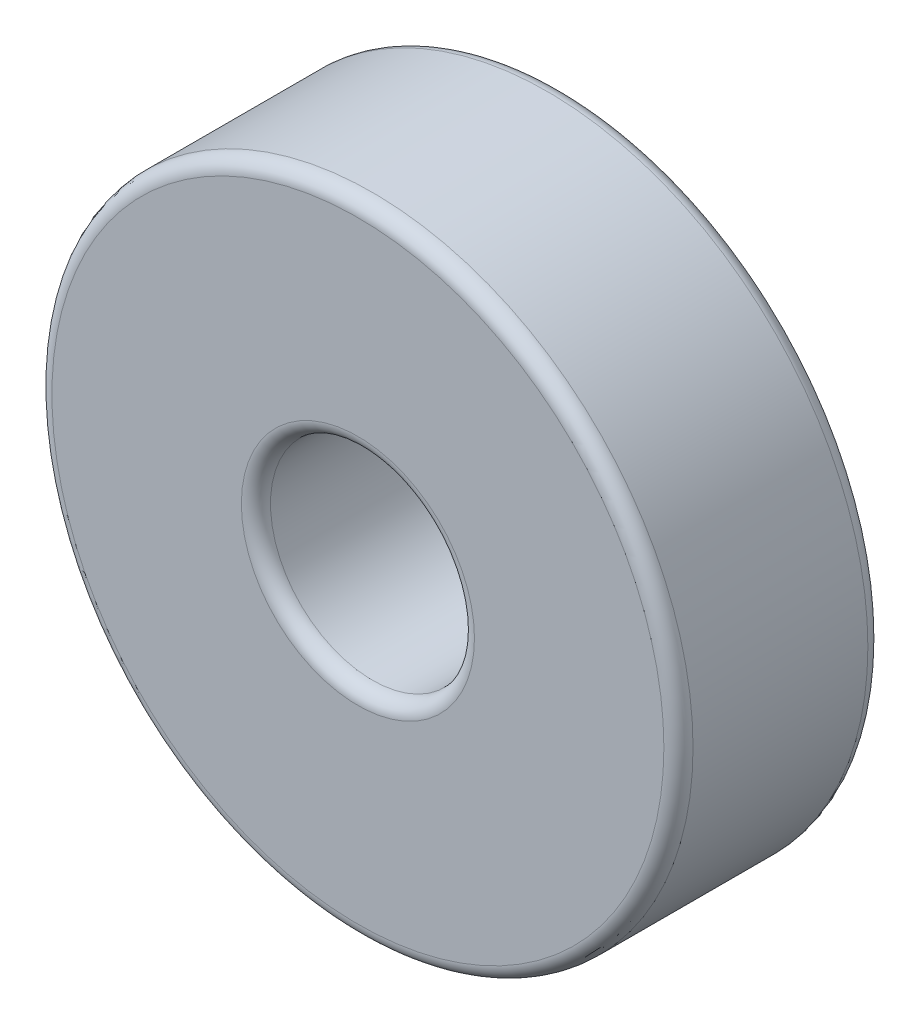
SolidWorks part; units mm, degrees
material "Хромистая нержавеющая сталь"
ref_plane "Спереди" through (0, 0, 0) normal (0, 0, 1) x (1, 0, 0)
ref_plane "Сверху" through (0, 0, 0) normal (0, 1, 0) x (1, 0, 0)
ref_plane "Справа" through (0, 0, 0) normal (1, 0, 0) x (0, 0, -1)
sketch "Эскиз1" plane through (0, 0, 0) normal (0, 0, 1) x (1, 0, 0)
  circle A0 centre (0, 0) radius 3.5
  circle A1 centre (0, 0) radius 11
  dimension "D1" = 7
  dimension "D2" = 22
extrude "Бобышка-Вытянуть1" add sketch "Эскиз1" along normal blind 7 contours A1 | A0
fillet "Скругление1" radius 0.5 4 edges at (3.5, 0, 0) (3.5, 0, 7) (11, 0, 0) (11, 0, 7)
